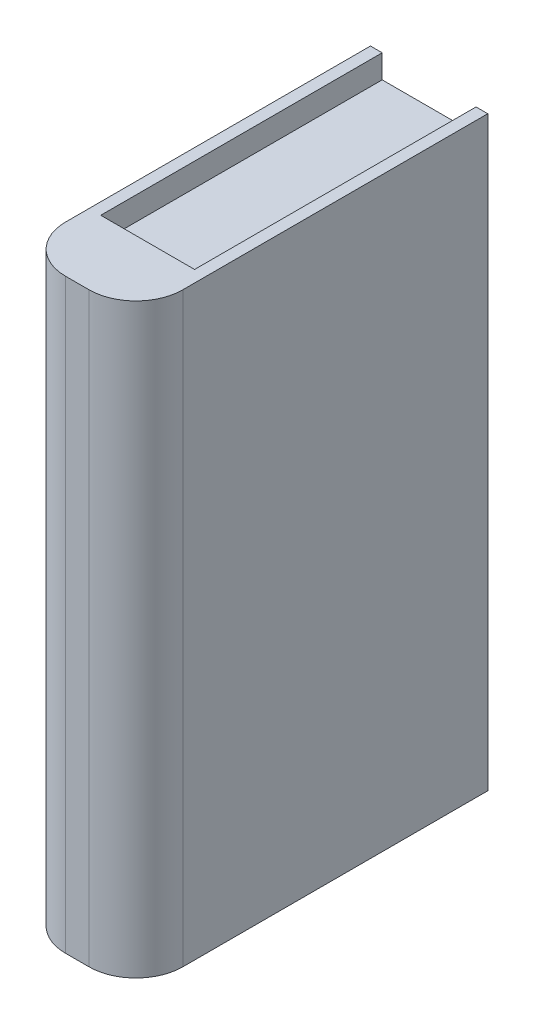
SolidWorks part; units mm, degrees
ref_plane "Front Plane" through (0, 0, 0) normal (0, 0, 1) x (1, 0, 0)
ref_plane "Top Plane" through (0, 0, 0) normal (0, 1, 0) x (1, 0, 0)
ref_plane "Right Plane" through (0, 0, 0) normal (1, 0, 0) x (0, 0, -1)
sketch "Sketch1" plane through (0, 0, 0) normal (1, 0, 0) x (0, 0, -1)
  line L1 (0, 0) -> (-15, 0)
  line L2 (0, 0) -> (0, 25)
  line L3 (0, 25) -> (-15, 25)
  line L4 (-15, 0) -> (-15, 25)
  dimension "D1" = 15
  dimension "D2" = 25
extrude "Boss-Extrude1" add sketch "Sketch1" along normal blind 5
fillet "Fillet1" radius 2 2 edges at (5, 12.5, 15) (0, 12.5, 15)
sketch "Sketch2" plane through (0, 25, 0) normal (0, 1, 0) x (1, 0, 0)
  line L0 (5, 0) -> (0, 0) construction
  line L1 (0.5, 0) -> (4.5, 0)
  line L2 (0.5, 0) -> (0.5, -12)
  line L3 (0.5, -12) -> (4.5, -12)
  line L4 (4.5, 0) -> (4.5, -12)
  line L5 (0, 0) -> (0, -13) construction
  line L6 (5, 0) -> (5, -13) construction
  dimension "D1" = 0.5
  dimension "D2" = 0.5
  dimension "D3" = 12
extrude "Cut-Extrude1" cut sketch "Sketch2" against normal blind 1
